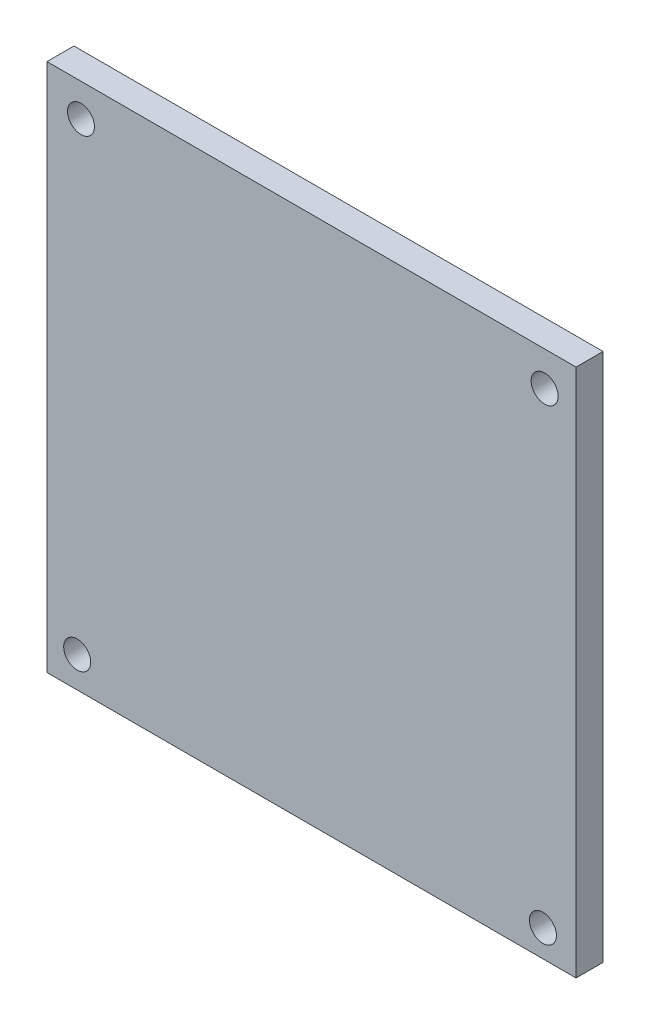
SolidWorks part; units mm, degrees
ref_plane "Front Plane" through (0, 0, 0) normal (0, 0, 1) x (1, 0, 0)
ref_plane "Top Plane" through (0, 0, 0) normal (0, 1, 0) x (1, 0, 0)
ref_plane "Right Plane" through (0, 0, 0) normal (1, 0, 0) x (0, 0, -1)
sketch "Sketch1" plane through (0, 0, 0) normal (0, 0, 1) x (1, 0, 0)
  line L1 (24.892, 24.892) -> (-24.892, 24.892)
  line L2 (24.892, 24.892) -> (24.892, -24.892)
  line L3 (24.892, -24.892) -> (-24.892, -24.892)
  line L4 (-24.892, 24.892) -> (-24.892, -24.892)
  line L5 (24.892, 24.892) -> (-24.892, -24.892) construction
  line L6 (24.892, -24.892) -> (-24.892, 24.892) construction
  point P0 (0, 0)
  dimension "D1" = 49.784
  dimension "D2" = 49.784
extrude "Boss-Extrude1" add sketch "Sketch1" along normal blind 2.54
sketch "Sketch2" plane through (0, 0, 2.54) normal (0, 0, 1) x (1, 0, 0)
  line L4 (-24.892, 24.892) -> (-24.892, -24.892)
  line L5 (-24.892, -24.892) -> (24.892, -24.892)
  line L6 (24.892, -24.892) -> (24.892, 24.892)
  line L7 (24.892, 24.892) -> (-24.892, 24.892)
  line L8 (-24.892, 24.892) -> (-24.892, -24.892)
  line L9 (-24.892, -24.892) -> (24.892, -24.892)
  line L10 (24.892, -24.892) -> (24.892, 24.892)
  line L11 (24.892, 24.892) -> (-24.892, 24.892)
  circle A0 centre (-22.0472, -22.0037) radius 1.27 construction
  circle A1 centre (-22.0472, -22.0037) radius 1.27
  circle A2 centre (-21.6885, 21.8185) radius 1.27 construction
  circle A3 centre (-21.6885, 21.8185) radius 1.27
  circle A4 centre (21.775, -22.3624) radius 1.27 construction
  circle A5 centre (21.775, -22.3624) radius 1.27
  circle A6 centre (21.9345, 21.6613) radius 1.27 construction
  circle A7 centre (21.9345, 21.6613) radius 1.27
  dimension "D1" = 0
extrude "Cut-Extrude1" cut sketch "Sketch2" against normal through all contours A3 | A1 | A5 | A7
